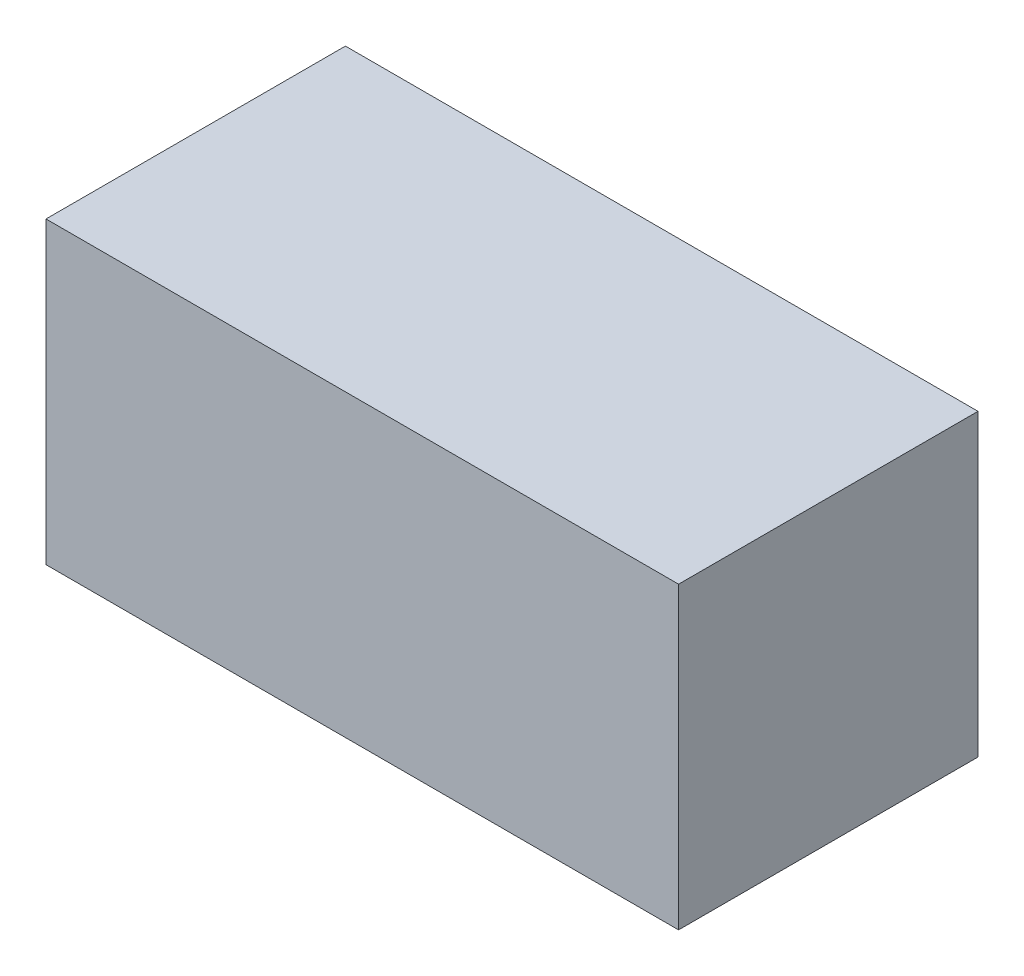
SolidWorks part; units mm, degrees
material "Rubber"
ref_plane "Front Plane" through (0, 0, 0) normal (0, 0, 1) x (1, 0, 0)
ref_plane "Top Plane" through (0, 0, 0) normal (0, 1, 0) x (1, 0, 0)
ref_plane "Right Plane" through (0, 0, 0) normal (1, 0, 0) x (0, 0, -1)
sketch "Sketch1" plane through (0, 0, 0) normal (0, 0, 1) x (1, 0, 0)
  line L1 (-37.5, -17.75) -> (37.5, -17.75)
  line L2 (-37.5, -17.75) -> (-37.5, 17.75)
  line L3 (-37.5, 17.75) -> (37.5, 17.75)
  line L4 (37.5, -17.75) -> (37.5, 17.75)
  line L5 (-37.5, -17.75) -> (37.5, 17.75) construction
  line L6 (-37.5, 17.75) -> (37.5, -17.75) construction
  point P0 (0, 0)
  dimension "D1" = 35.5
  dimension "D2" = 75
extrude "Boss-Extrude1" add sketch "Sketch1" along normal blind 35.5
